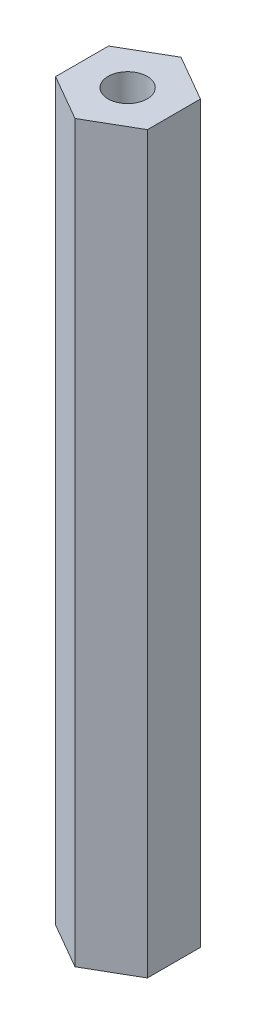
SolidWorks part; units mm, degrees
ref_plane "Front Plane" through (0, 0, 0) normal (0, 0, 1) x (1, 0, 0)
ref_plane "Top Plane" through (0, 0, 0) normal (0, 1, 0) x (1, 0, 0)
ref_plane "Right Plane" through (0, 0, 0) normal (1, 0, 0) x (0, 0, -1)
sketch "Sketch1" plane through (0, 0, 0) normal (0, 1, 0) x (1, 0, 0)
  line L0 (0, 0) -> (0, 3.6662) construction
  line L1 (3.175, 1.8331) -> (0, 3.6662)
  line L2 (0, 3.6662) -> (-3.175, 1.8331)
  line L3 (-3.175, 1.8331) -> (-3.175, -1.8331)
  line L4 (-3.175, -1.8331) -> (0, -3.6662)
  line L5 (0, -3.6662) -> (3.175, -1.8331)
  line L6 (3.175, -1.8331) -> (3.175, 1.8331)
  circle A0 centre (0, 0) radius 3.175 construction
  dimension "D1" = 6.35
extrude "Boss-Extrude1" add sketch "Sketch1" along normal blind 50.8
ref_point "Point1"
ref_point "Point2"
hole_wizard "#6-32 Tapped Hole1" positions "Sketch7" profile "Sketch6" tap size "#6-32" standard "Ansi Inch"
sketch "Sketch7" plane through (0, 50.8, 0) normal (0, 1, 0) x (-1, 0, 0)
  point P0 (0.0235, 0.0024)
sketch "Sketch6" plane through (-0.0235, 50.8, 0.0024) normal (1, 0, 0) x (0, 0, 1)
  line L0 (0, 0) -> (0, 10.2107)
  line L1 (0, 10.2107) -> (1.3525, 9.398)
  line L2 (1.3525, 9.398) -> (1.3525, 0)
  line L5 (1.3525, 0) -> (0, 0)
  line L10 (0, 10.2107) -> (-1.3526, 9.398) construction
  line L11 (0, -6.35) -> (0, 107.95) construction
  dimension "Tap Drill Dia." = 2.7051
  dimension "Tap Drill Depth" = 9.398
  dimension "Drill Angle" = 118
cosmetic thread "Hole Thread1" parameters "D1"=7.112, "D2"=3.5052
hole_wizard "#6-32 Tapped Hole2" positions "Sketch9" profile "Sketch8" tap size "#6-32" standard "Ansi Inch"
sketch "Sketch9" plane through (0, 0, 0) normal (0, -1, 0) x (1, 0, 0)
  point P0 (0.0211, 0.0735)
sketch "Sketch8" plane through (0.0211, 0, 0.0735) normal (1, 0, 0) x (0, 0, -1)
  line L0 (0, 0) -> (0, 10.2107)
  line L1 (0, 10.2107) -> (1.3525, 9.398)
  line L2 (1.3525, 9.398) -> (1.3525, 0)
  line L5 (1.3525, 0) -> (0, 0)
  line L10 (0, 10.2107) -> (-1.3526, 9.398) construction
  line L11 (0, -6.35) -> (0, 107.95) construction
  dimension "Tap Drill Dia." = 2.7051
  dimension "Tap Drill Depth" = 9.398
  dimension "Drill Angle" = 118
cosmetic thread "Hole Thread2" parameters "D1"=7.112, "D2"=3.5052
